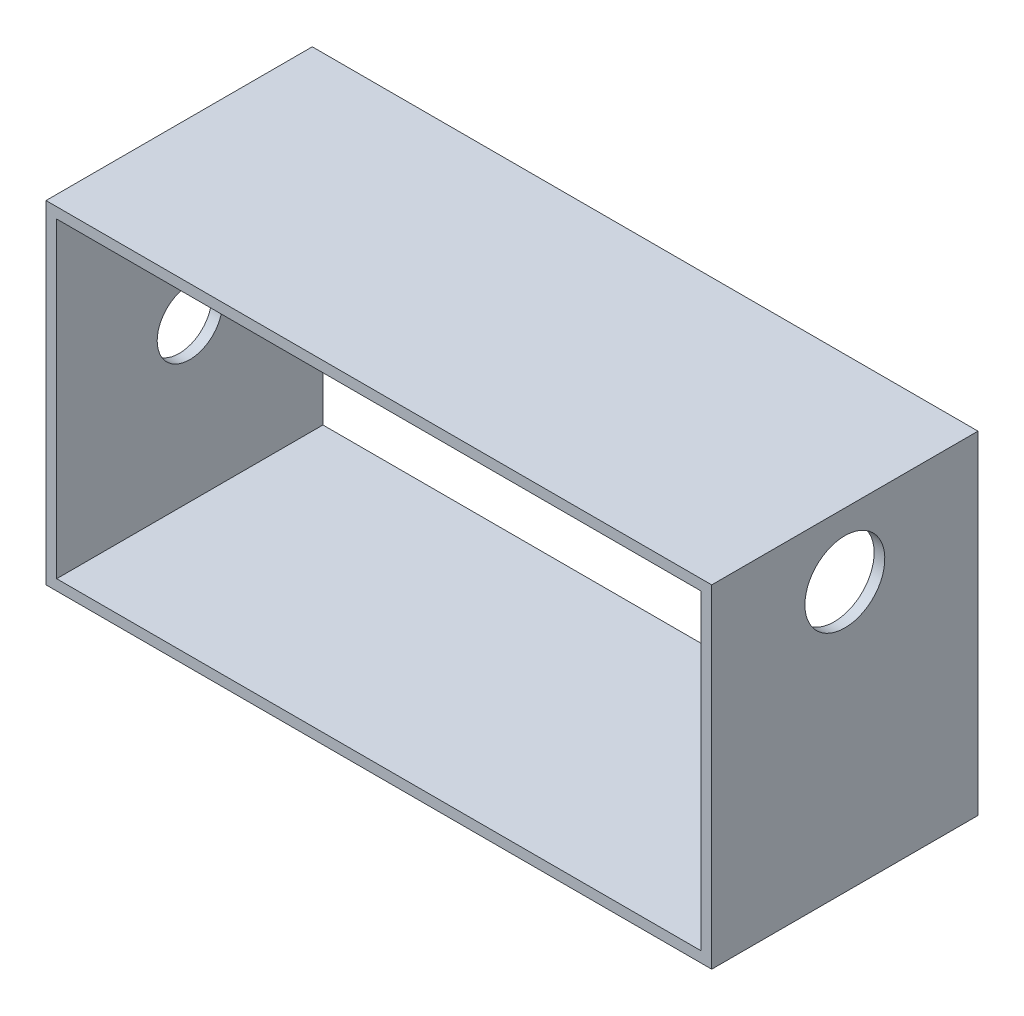
SolidWorks part; units mm, degrees
ref_plane "Ebene vorne" through (0, 0, 0) normal (0, 0, 1) x (1, 0, 0)
ref_plane "Ebene oben" through (0, 0, 0) normal (0, 1, 0) x (1, 0, 0)
ref_plane "Ebene rechts" through (0, 0, 0) normal (1, 0, 0) x (0, 0, -1)
sketch "Skizze1" plane through (0, 0, 0) normal (0, 0, 1) x (1, 0, 0)
  line L1 (0, 125) -> (250, 125)
  line L2 (0, 125) -> (0, 0)
  line L3 (0, 0) -> (250, 0)
  line L4 (250, 125) -> (250, 0)
  line L5 (246, 121) -> (4, 121)
  line L6 (246, 121) -> (246, 4)
  line L7 (246, 4) -> (4, 4)
  line L8 (4, 121) -> (4, 4)
  dimension "D1" = 250
  dimension "D2" = 125
  dimension "D3" = 4
  dimension "D4" = 4
  dimension "D5" = 4
  dimension "D6" = 4
extrude "Aufsatz-Linear austragen1" add sketch "Skizze1" along normal blind 100
sketch "Skizze2" plane through (0, 0, 0) normal (-1, 0, 0) x (0, 0, 1)
  line L0 (0, 125) -> (100, 0) construction
  circle A0 centre (50, 62.5) radius 12.25
extrude "Schnitt-Linear austragen1" cut sketch "Skizze2" against normal blind 10
sketch "Skizze3" plane through (246, 0, 0) normal (-1, 0, 0) x (0, 0, 1)
  line L0 (0, 101) -> (50, 101) construction
  line L1 (0, 4) -> (0, 121) construction
  line L2 (50, 101) -> (100, 101) construction
  line L3 (100, 4) -> (100, 121) construction
  line L4 (50, 101) -> (50, 121) construction
  line L5 (100, 121) -> (0, 121) construction
  circle A0 centre (50, 101) radius 15
extrude "Schnitt-Linear austragen2" cut sketch "Skizze3" against normal blind 10
